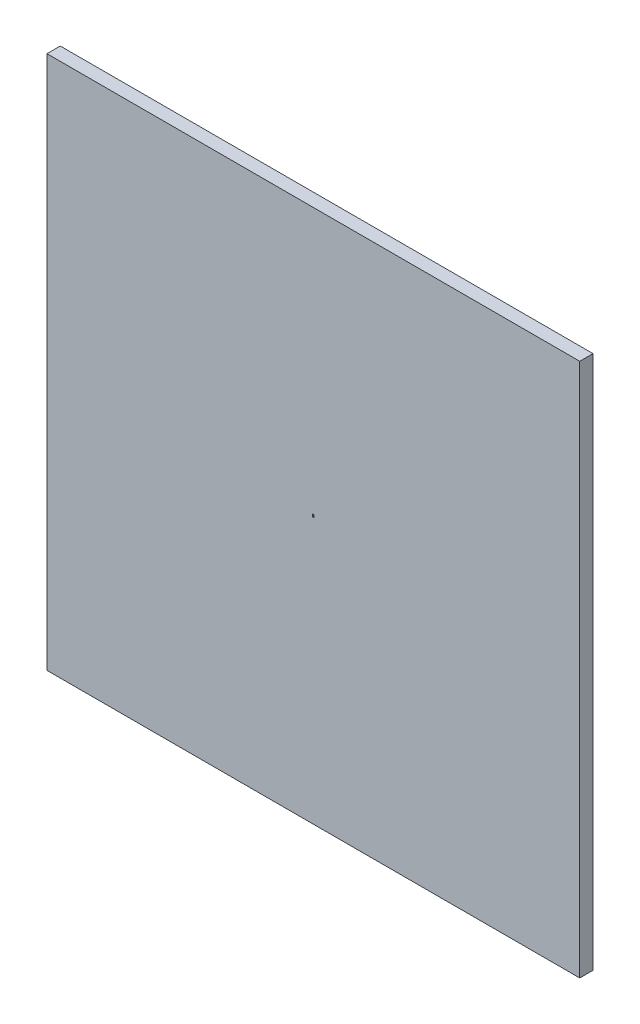
SolidWorks part; units mm, degrees
ref_plane "前基準面" through (0, 0, 0) normal (0, 0, 1) x (1, 0, 0)
ref_plane "上基準面" through (0, 0, 0) normal (0, 1, 0) x (1, 0, 0)
ref_plane "右基準面" through (0, 0, 0) normal (1, 0, 0) x (0, 0, -1)
sketch "草圖1" plane through (0, 0, 0) normal (0, 0, 1) x (1, 0, 0)
  line L1 (-500, -1000) -> (500, -1000)
  line L2 (-500, -1000) -> (-500, 1000)
  line L3 (-500, 1000) -> (500, 1000)
  line L4 (500, -1000) -> (500, 1000)
  line L5 (-500, -1000) -> (500, 1000) construction
  line L6 (-500, 1000) -> (500, -1000) construction
  line L7 (-200500, -201000) -> (200500, -201000)
  line L8 (-200500, -201000) -> (-200500, 201000)
  line L9 (-200500, 201000) -> (200500, 201000)
  line L10 (200500, -201000) -> (200500, 201000)
  line L11 (-200500, -201000) -> (200500, 201000) construction
  line L12 (-200500, 201000) -> (200500, -201000) construction
  point P0 (0, 0)
  point P6 (0, 0)
  dimension "D1" = 2000
  dimension "D2" = 1000
  dimension "D3" = 200000
  dimension "D4" = 200000
extrude "填料-伸長1" add sketch "草圖1" along normal blind 10000
